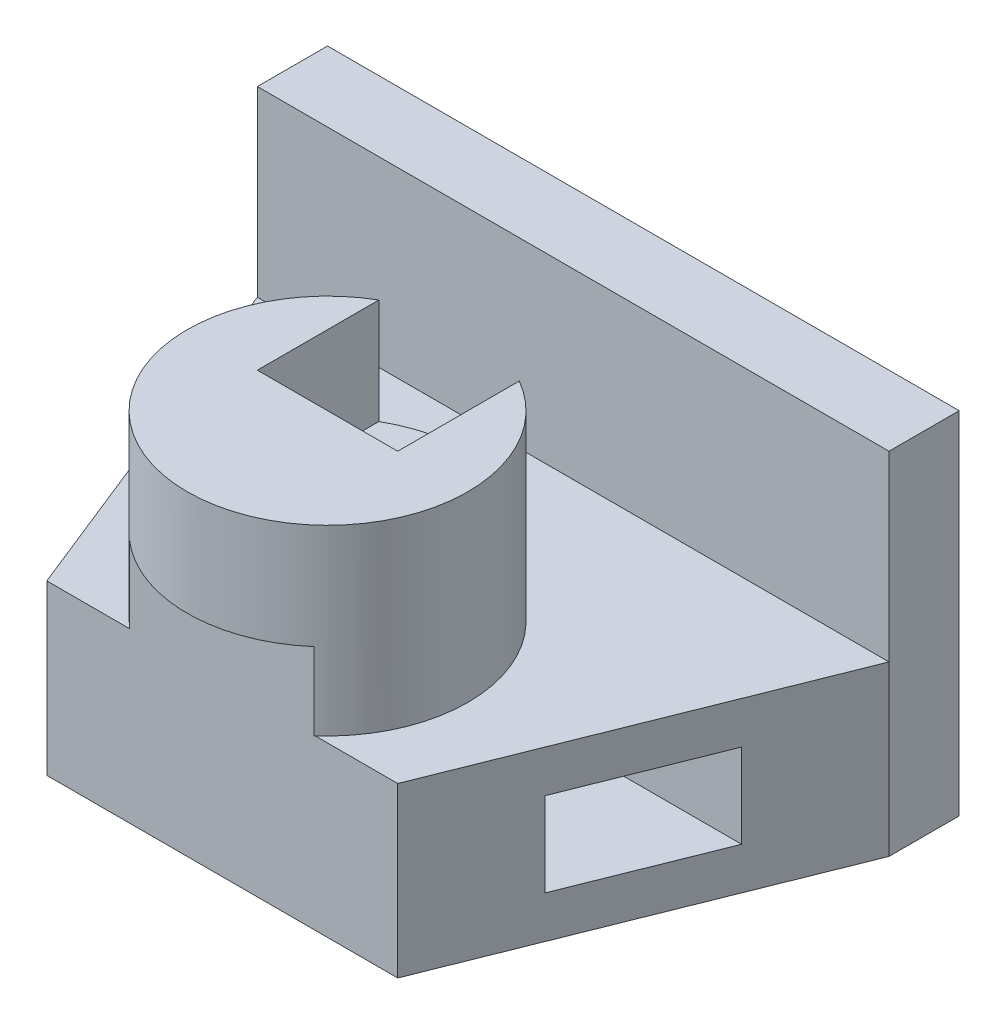
SolidWorks part; units mm, degrees
ref_plane "Front Plane" through (0, 0, 0) normal (0, 0, 1) x (1, 0, 0)
ref_plane "Top Plane" through (0, 0, 0) normal (0, 1, 0) x (1, 0, 0)
ref_plane "Right Plane" through (0, 0, 0) normal (1, 0, 0) x (0, 0, -1)
sketch "Sketch3" plane through (0, 0, 0) normal (0, 0, 1) x (1, 0, 0)
  line L1 (-45, -25) -> (45, -25)
  line L2 (-45, -25) -> (-45, 25)
  line L3 (-45, 25) -> (45, 25)
  line L4 (45, -25) -> (45, 25)
  line L5 (-45, -25) -> (45, 25) construction
  line L6 (-45, 25) -> (45, -25) construction
  point P0 (0, 0)
  dimension "D1" = 50
  dimension "D2" = 90
extrude "Boss-Extrude1" add sketch "Sketch3" along normal blind 10
sketch "Sketch4" plane through (0, -25, 0) normal (0, -1, 0) x (1, 0, 0)
  line L0 (45, 10) -> (-45, 10)
  line L1 (-45, 10) -> (-25, 60)
  line L2 (-25, 60) -> (25, 60)
  line L3 (25, 60) -> (45, 10)
  dimension "D1" = 50
  dimension "D2" = 50
extrude "Boss-Extrude2" add sketch "Sketch4" against normal blind 24
sketch "Sketch5" plane through (0, -1, 0) normal (0, 1, 0) x (1, 0, 0)
  line L0 (45, 0) -> (-45, 0) construction
  circle A0 centre (0, -45) radius 20
  dimension "D2" = 40
  dimension "D1" = 45
  dimension "D3" = 25
extrude "Boss-Extrude3" add sketch "Sketch5" along normal blind 26
sketch "Sketch6" plane through (0, 25, 0) normal (0, 1, 0) x (1, 0, 0)
  line L0 (45, 0) -> (-45, 0) construction
  line L1 (-10, -45) -> (10, -45)
  line L2 (-10, -45) -> (-10, -17.8896)
  line L3 (-10, -17.8896) -> (10, -17.8896)
  line L4 (10, -45) -> (10, -17.8896)
  line L5 (-10, -45) -> (10, -17.8896) construction
  line L6 (-10, -17.8896) -> (10, -45) construction
  point P0 (0, -31.4448)
  dimension "D1" = 45
  dimension "D2" = 25
  dimension "D3" = 20
extrude "Cut-Extrude1" cut sketch "Sketch6" against normal blind 15
sketch "Sketch7" plane through (0, -25, 0) normal (0, -1, 0) x (1, 0, 0)
  line L1 (-13.2288, 60) -> (13.1404, 60)
  line L2 (-13.2288, 60) -> (-13.2288, 70.7187)
  line L3 (-13.2288, 70.7187) -> (13.1404, 70.7187)
  line L4 (13.1404, 60) -> (13.1404, 70.7187)
  line L5 (-13.2288, 60) -> (13.1404, 70.7187) construction
  line L6 (-13.2288, 70.7187) -> (13.1404, 60) construction
  point P4 (-0.0442, 65.3594)
extrude "Cut-Extrude2" cut sketch "Sketch7" against normal blind 35
sketch "Sketch9" plane through (45, 0, 0) normal (1, 0, 0) x (0, 0, -1)
  line L0 (-10, -25) -> (-10, -1) construction
  line L1 (-45, -7) -> (-25, -7)
  line L2 (-45, -7) -> (-45, -19)
  line L3 (-45, -19) -> (-25, -19)
  line L4 (-25, -7) -> (-25, -19)
  line L5 (-45, -7) -> (-25, -19) construction
  line L6 (-45, -19) -> (-25, -7) construction
  line L7 (-10, -1) -> (-60, -1) construction
  point P4 (-35, -13)
  dimension "D1" = 20
  dimension "D2" = 15
  dimension "D3" = 12
  dimension "D4" = 6
extrude "Cut-Extrude3" cut sketch "Sketch9" against normal through all
